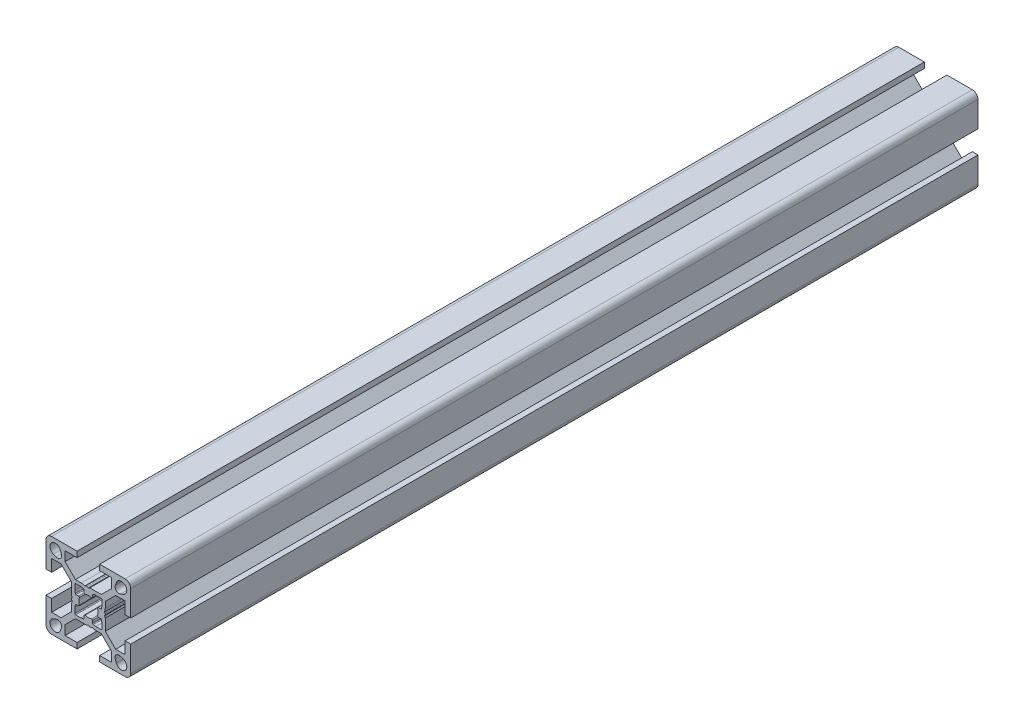
SolidWorks part; units mm, degrees
material "1060 Alloy"
ref_plane "Front Plane" through (0, 0, 0) normal (0, 0, 1) x (1, 0, 0)
ref_plane "Top Plane" through (0, 0, 0) normal (0, 1, 0) x (1, 0, 0)
ref_plane "Right Plane" through (0, 0, 0) normal (1, 0, 0) x (0, 0, -1)
sketch "Model" plane through (0, 0, 0) normal (0, 0, 1) x (1, 0, 0)
  line L0 (-13.695, -11.7) -> (-9.705, -11.7) construction
  line L1 (-11.7, -13.695) -> (-11.7, -9.705) construction
  line L2 (9.705, -11.7) -> (13.695, -11.7) construction
  line L3 (11.7, -13.695) -> (11.7, -9.705) construction
  line L4 (-13.695, 11.7) -> (-9.705, 11.7) construction
  line L5 (-11.7, 9.705) -> (-11.7, 13.695) construction
  line L6 (9.705, 11.7) -> (13.695, 11.7) construction
  line L7 (11.7, 9.705) -> (11.7, 13.695) construction
  line L8 (-15, 13) -> (-15, 4)
  line L9 (-15, 4) -> (-13, 4)
  line L10 (-13, 4) -> (-13, 8.25)
  line L11 (-13, 8.25) -> (-9.6642, 8.25)
  line L12 (-9.6642, 8.25) -> (-6, 4.5858)
  line L13 (-6, 4.5858) -> (-6, 0.5196)
  line L14 (-6, 0.5196) -> (-5.7, 0)
  line L15 (-5.7, 0) -> (-5.933, -0.4036)
  line L16 (-5.933, -0.9036) -> (-5.751, -1.2189)
  line L17 (-5.751, -1.2189) -> (-6, -2.5)
  line L18 (-6, -2.5) -> (-6, -4.5858)
  line L19 (-6, -4.5858) -> (-9.6642, -8.25)
  line L20 (-9.6642, -8.25) -> (-13, -8.25)
  line L21 (-13, -8.25) -> (-13, -4)
  line L22 (-13, -4) -> (-15, -4)
  line L23 (-15, -4) -> (-15, -13)
  line L24 (-13, -15) -> (-4, -15)
  line L25 (-4, -15) -> (-4, -13)
  line L26 (-4, -13) -> (-8.25, -13)
  line L27 (-8.25, -13) -> (-8.25, -9.6642)
  line L28 (-8.25, -9.6642) -> (-4.5858, -6)
  line L29 (-4.5858, -6) -> (-0.5196, -6)
  line L30 (-0.5196, -6) -> (0, -5.7)
  line L31 (0, -5.7) -> (0.4036, -5.933)
  line L32 (0.9036, -5.933) -> (1.2189, -5.751)
  line L33 (1.2189, -5.751) -> (2.5, -6)
  line L34 (2.5, -6) -> (4.5858, -6)
  line L35 (4.5858, -6) -> (8.25, -9.6642)
  line L36 (8.25, -9.6642) -> (8.25, -13)
  line L37 (8.25, -13) -> (4, -13)
  line L38 (4, -13) -> (4, -15)
  line L39 (4, -15) -> (13, -15)
  line L40 (15, -13) -> (15, -4)
  line L41 (15, -4) -> (13, -4)
  line L42 (13, -4) -> (13, -8.25)
  line L43 (13, -8.25) -> (9.6642, -8.25)
  line L44 (9.6642, -8.25) -> (6, -4.5858)
  line L45 (6, -4.5858) -> (6, -0.5196)
  line L46 (6, -0.5196) -> (5.7, 0)
  line L47 (5.7, 0) -> (5.933, 0.4036)
  line L48 (5.933, 0.9036) -> (5.751, 1.2189)
  line L49 (5.751, 1.2189) -> (6, 2.5)
  line L50 (6, 2.5) -> (6, 4.5858)
  line L51 (6, 4.5858) -> (9.6642, 8.25)
  line L52 (9.6642, 8.25) -> (13, 8.25)
  line L53 (13, 8.25) -> (13, 4)
  line L54 (13, 4) -> (15, 4)
  line L55 (15, 4) -> (15, 13)
  line L56 (13, 15) -> (4, 15)
  line L57 (4, 15) -> (4, 13)
  line L58 (4, 13) -> (8.25, 13)
  line L59 (8.25, 13) -> (8.25, 9.6642)
  line L60 (8.25, 9.6642) -> (4.5858, 6)
  line L61 (4.5858, 6) -> (0.5196, 6)
  line L62 (0.5196, 6) -> (0, 5.7)
  line L63 (0, 5.7) -> (-0.4036, 5.933)
  line L64 (-0.9036, 5.933) -> (-1.2189, 5.751)
  line L65 (-1.2189, 5.751) -> (-2.5, 6)
  line L66 (-2.5, 6) -> (-4.5858, 6)
  line L67 (-4.5858, 6) -> (-8.25, 9.6642)
  line L68 (-8.25, 9.6642) -> (-8.25, 13)
  line L69 (-8.25, 13) -> (-4, 13)
  line L70 (-4, 13) -> (-4, 15)
  line L71 (-4, 15) -> (-13, 15)
  line L72 (9.9189, 12.3615) -> (9.5391, 11.3389)
  line L73 (11.3389, 9.5391) -> (12.3615, 9.9189)
  line L74 (12.3615, -9.9189) -> (11.3389, -9.5391)
  line L75 (9.5391, -11.3389) -> (9.9189, -12.3615)
  line L76 (-9.5391, 11.3389) -> (-9.9189, 12.3615)
  line L77 (-12.3615, 9.9189) -> (-11.3389, 9.5391)
  line L78 (-11.3389, -9.5391) -> (-12.3615, -9.9189)
  line L79 (-9.9189, -12.3615) -> (-9.5391, -11.3389)
  line L80 (1.5, 4.3359) -> (1.5, 3.5)
  line L81 (-4.8, -2.6444) -> (-4.8, -4.5)
  line L82 (-4.6303, -1.7428) -> (-4.7945, -2.5872)
  line L83 (-3.5, -1.5) -> (-4.3359, -1.5)
  line L84 (-4.3359, 1.5) -> (-3.5, 1.5)
  line L85 (-4.7945, 2.5872) -> (-4.6303, 1.7428)
  line L86 (-4.8, 4.5) -> (-4.8, 2.6444)
  line L87 (-2.6444, 4.8) -> (-4.5, 4.8)
  line L88 (-1.7428, 4.6303) -> (-2.5872, 4.7945)
  line L89 (-1.5, 3.5) -> (-1.5, 4.3359)
  line L90 (2.5872, 4.7945) -> (1.7428, 4.6303)
  line L91 (4.5, 4.8) -> (2.6444, 4.8)
  line L92 (4.8, 2.6444) -> (4.8, 4.5)
  line L93 (4.6303, 1.7428) -> (4.7945, 2.5872)
  line L94 (3.5, 1.5) -> (4.3359, 1.5)
  line L95 (4.3359, -1.5) -> (3.5, -1.5)
  line L96 (4.7945, -2.5872) -> (4.6303, -1.7428)
  line L97 (4.8, -4.5) -> (4.8, -2.6444)
  line L98 (2.6444, -4.8) -> (4.5, -4.8)
  line L99 (1.7428, -4.6303) -> (2.5872, -4.7945)
  line L100 (1.5, -3.5) -> (1.5, -4.3359)
  line L101 (-1.5, -4.3359) -> (-1.5, -3.5)
  line L102 (-2.5872, -4.7945) -> (-1.7428, -4.6303)
  line L103 (-4.5, -4.8) -> (-2.6444, -4.8)
  arc A0 (-5.933, -0.4036) -> (-5.933, -0.9036) centre (-5.5, -0.6536) ccw
  arc A1 (-15, -13) -> (-13, -15) centre (-13, -13) ccw
  arc A2 (0.4036, -5.933) -> (0.9036, -5.933) centre (0.6536, -5.5) ccw
  arc A3 (13, -15) -> (15, -13) centre (13, -13) ccw
  arc A4 (5.933, 0.4036) -> (5.933, 0.9036) centre (5.5, 0.6536) ccw
  arc A5 (15, 13) -> (13, 15) centre (13, 13) ccw
  arc A6 (-0.4036, 5.933) -> (-0.9036, 5.933) centre (-0.6536, 5.5) ccw
  arc A7 (12.3615, 9.9189) -> (9.9189, 12.3615) centre (11.7, 11.7) ccw
  arc A8 (9.9189, -12.3615) -> (12.3615, -9.9189) centre (11.7, -11.7) ccw
  arc A9 (-11.3389, 9.5391) -> (-9.5391, 11.3389) centre (-10.8515, 10.8515) ccw
  arc A10 (-9.5391, -11.3389) -> (-11.3389, -9.5391) centre (-10.8515, -10.8515) ccw
  arc A11 (9.5391, 11.3389) -> (11.3389, 9.5391) centre (10.8515, 10.8515) ccw
  arc A12 (11.3389, -9.5391) -> (9.5391, -11.3389) centre (10.8515, -10.8515) ccw
  arc A13 (-9.9189, 12.3615) -> (-12.3615, 9.9189) centre (-11.7, 11.7) ccw
  arc A14 (-12.3615, -9.9189) -> (-9.9189, -12.3615) centre (-11.7, -11.7) ccw
  arc A15 (-13, 15) -> (-15, 13) centre (-13, 13) ccw
  arc A16 (-4.7945, -2.5872) -> (-4.8, -2.6444) centre (-4.5, -2.6444) ccw
  arc A17 (-4.3359, -1.5) -> (-4.6303, -1.7428) centre (-4.3359, -1.8) ccw
  arc A18 (-3.5, -1.5) -> (-3.2162, -1.1027) centre (-3.5, -1.2) ccw
  arc A19 (-3.2162, 1.1027) -> (-3.2162, -1.1027) centre (0, 0) ccw
  arc A20 (-3.2162, 1.1027) -> (-3.5, 1.5) centre (-3.5, 1.2) ccw
  arc A21 (-4.6303, 1.7428) -> (-4.3359, 1.5) centre (-4.3359, 1.8) ccw
  arc A22 (-4.8, 2.6444) -> (-4.7945, 2.5872) centre (-4.5, 2.6444) ccw
  arc A23 (-4.5, 4.8) -> (-4.8, 4.5) centre (-4.5, 4.5) ccw
  arc A24 (-2.5872, 4.7945) -> (-2.6444, 4.8) centre (-2.6444, 4.5) ccw
  arc A25 (-1.5, 4.3359) -> (-1.7428, 4.6303) centre (-1.8, 4.3359) ccw
  arc A26 (-1.5, 3.5) -> (-1.1027, 3.2162) centre (-1.2, 3.5) ccw
  arc A27 (1.1027, 3.2162) -> (-1.1027, 3.2162) centre (0, 0) ccw
  arc A28 (1.1027, 3.2162) -> (1.5, 3.5) centre (1.2, 3.5) ccw
  arc A29 (1.7428, 4.6303) -> (1.5, 4.3359) centre (1.8, 4.3359) ccw
  arc A30 (2.6444, 4.8) -> (2.5872, 4.7945) centre (2.6444, 4.5) ccw
  arc A31 (4.8, 4.5) -> (4.5, 4.8) centre (4.5, 4.5) ccw
  arc A32 (4.7945, 2.5872) -> (4.8, 2.6444) centre (4.5, 2.6444) ccw
  arc A33 (4.3359, 1.5) -> (4.6303, 1.7428) centre (4.3359, 1.8) ccw
  arc A34 (3.5, 1.5) -> (3.2162, 1.1027) centre (3.5, 1.2) ccw
  arc A35 (3.2162, -1.1027) -> (3.2162, 1.1027) centre (0, 0) ccw
  arc A36 (3.2162, -1.1027) -> (3.5, -1.5) centre (3.5, -1.2) ccw
  arc A37 (4.6303, -1.7428) -> (4.3359, -1.5) centre (4.3359, -1.8) ccw
  arc A38 (4.8, -2.6444) -> (4.7945, -2.5872) centre (4.5, -2.6444) ccw
  arc A39 (4.5, -4.8) -> (4.8, -4.5) centre (4.5, -4.5) ccw
  arc A40 (2.5872, -4.7945) -> (2.6444, -4.8) centre (2.6444, -4.5) ccw
  arc A41 (1.5, -4.3359) -> (1.7428, -4.6303) centre (1.8, -4.3359) ccw
  arc A42 (1.5, -3.5) -> (1.1027, -3.2162) centre (1.2, -3.5) ccw
  arc A43 (-1.1027, -3.2162) -> (1.1027, -3.2162) centre (0, 0) ccw
  arc A44 (-1.1027, -3.2162) -> (-1.5, -3.5) centre (-1.2, -3.5) ccw
  arc A45 (-1.7428, -4.6303) -> (-1.5, -4.3359) centre (-1.8, -4.3359) ccw
  arc A46 (-2.6444, -4.8) -> (-2.5872, -4.7945) centre (-2.6444, -4.5) ccw
  arc A47 (-4.8, -4.5) -> (-4.5, -4.8) centre (-4.5, -4.5) ccw
extrude "Boss-Extrude1" add sketch "Model" along normal blind 300
